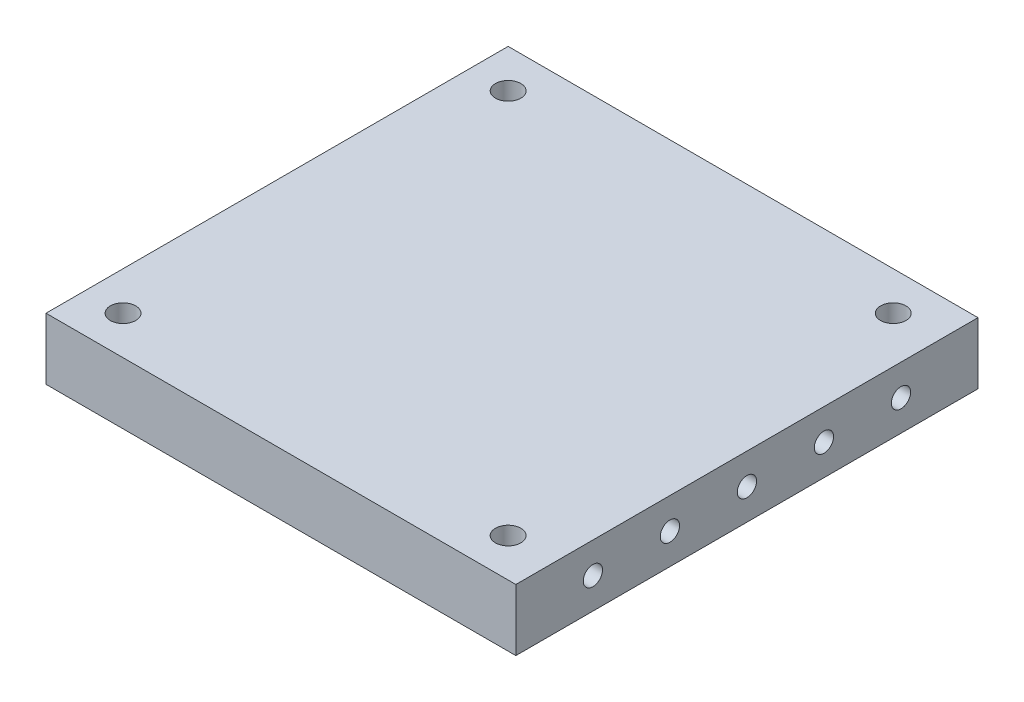
SolidWorks part; units mm, degrees
other "标注1"
sketch "草图6" plane through (0, 59, 0) normal (-0.0264, 0.2089, -0.9776) x (-0.9996, -0.01, 0.0249)
ref_plane "前视基准面" through (0, 0, 0) normal (0, 0, 1) x (1, 0, 0)
ref_plane "上视基准面" through (0, 0, 0) normal (0, 1, 0) x (1, 0, 0)
ref_plane "右视基准面" through (0, 0, 0) normal (1, 0, 0) x (0, 0, -1)
other "Configuration Table"
sketch "草图1" plane through (0, 0, 0) normal (0, 1, 0) x (1, 0, 0)
  line L1 (0, 0) -> (60, 0)
  line L2 (0, 0) -> (0, -60)
  line L3 (0, -60) -> (60, -60)
  line L4 (60, 0) -> (60, -60)
  dimension "D1" = 60
  dimension "D2" = 60
extrude "凸台-拉伸1" add sketch "草图1" along normal blind 8
sketch "草图2" plane through (0, 8, 0) normal (0, 1, 0) x (1, 0, 0)
  line L0 (5, -5) -> (5, 0) construction
  line L1 (60, 0) -> (0, 0) construction
  line L2 (5, -5) -> (0, -5) construction
  line L3 (0, 0) -> (0, -60) construction
  line L4 (5, -5) -> (5, -55) construction
  line L5 (5, -55) -> (55, -55) construction
  line L6 (55, -55) -> (55, -5) construction
  line L7 (55, -5) -> (5, -5) construction
  line L8 (55, -55) -> (60, -55) construction
  line L9 (60, -60) -> (60, 0) construction
  line L10 (55, -55) -> (55, -60) construction
  line L11 (0, -60) -> (60, -60) construction
  circle A0 centre (5, -5) radius 1.65
  circle A1 centre (55, -5) radius 1.65
  circle A2 centre (5, -55) radius 1.65
  circle A3 centre (55, -55) radius 1.65
  dimension "D2" = 3.3
  dimension "D1" = 50
extrude "切除-拉伸1" cut sketch "草图2" against normal blind 8
sketch "草图3" plane through (0, 8, 0) normal (0, 1, 0) x (1, 0, 0)
  line L1 (60, -60) -> (61, -60)
  line L2 (60, -60) -> (60, 0)
  line L3 (60, 0) -> (61, 0)
  line L4 (61, -60) -> (61, 0)
  dimension "D1" = 1
extrude "凸台-拉伸2" add sketch "草图3" against normal blind 8
sketch "草图7" plane through (61, 0, 0) normal (1, 0, 0) x (0, 0, -1)
  line L0 (-60, 4) -> (-50, 4) construction
  line L3 (-60, 0) -> (-60, 8) construction
  line L4 (-50, 4) -> (-40, 4) construction
  line L5 (-40, 4) -> (-30, 4) construction
  line L6 (-30, 4) -> (-20, 4) construction
  line L8 (-10, 4) -> (0, 4) construction
  line L9 (0, 0) -> (0, 8) construction
  line L10 (-20, 4) -> (-10, 4) construction
  circle A0 centre (-50, 4) radius 1.25
  circle A1 centre (-40, 4) radius 1.25
  circle A2 centre (-30, 4) radius 1.25
  circle A3 centre (-10, 4) radius 1.25
  circle A4 centre (-20, 4) radius 1.25
  dimension "D1" = 2.5
  dimension "D2" = 10
extrude "切除-拉伸2" cut sketch "草图7" against normal blind 9
